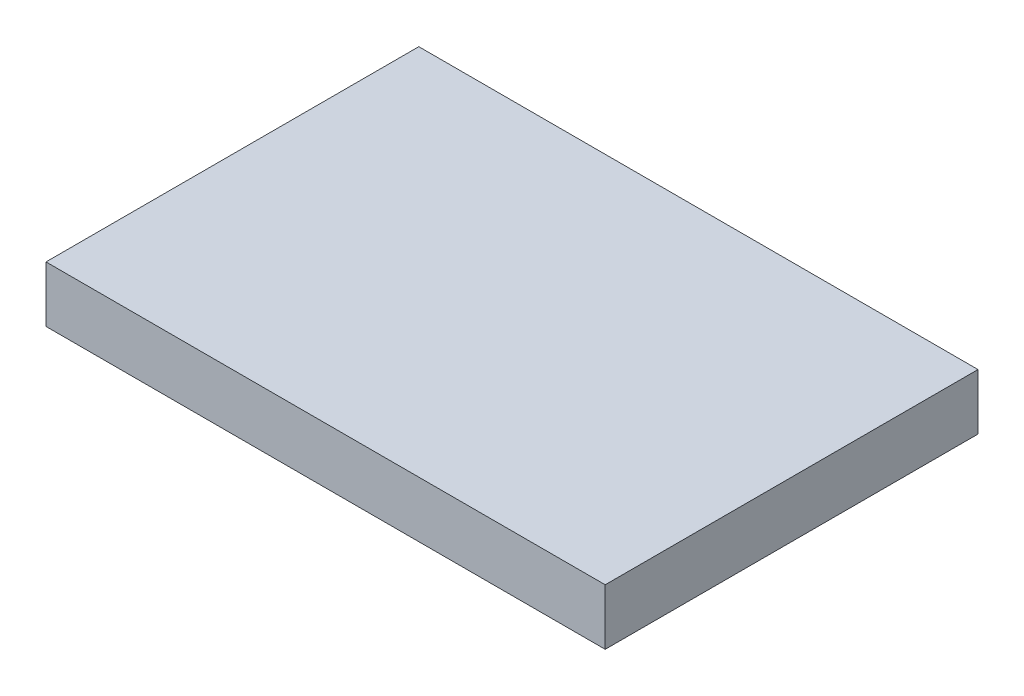
SolidWorks part; units mm, degrees
material "Pine"
ref_plane "Front Plane" through (0, 0, 0) normal (0, 0, 1) x (1, 0, 0)
ref_plane "Top Plane" through (0, 0, 0) normal (0, 1, 0) x (1, 0, 0)
ref_plane "Right Plane" through (0, 0, 0) normal (1, 0, 0) x (0, 0, -1)
sketch "Sketch1" plane through (0, 0, 0) normal (0, 1, 0) x (1, 0, 0)
  line L0 (0, -100) -> (0, 100) construction
  line L2 (-250, -100) -> (50, -100)
  line L3 (-250, -100) -> (-250, 100)
  line L4 (-250, 100) -> (50, 100)
  line L5 (50, -100) -> (50, 100)
  dimension "D1" = 50
  dimension "D2" = 300
  dimension "D3" = 200
extrude "Boss-Extrude1" add sketch "Sketch1" along normal blind 30
